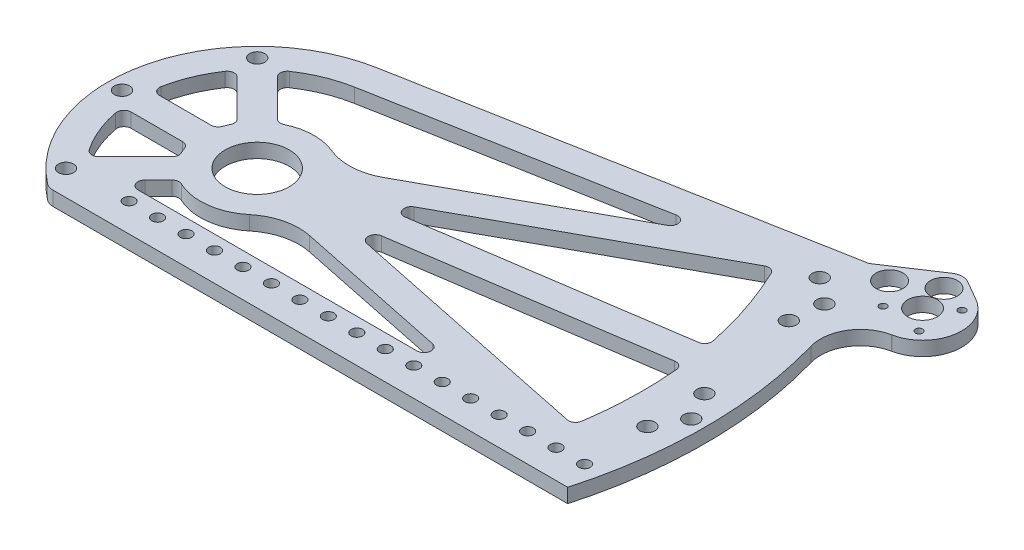
SolidWorks part; units mm, degrees
ref_plane "Front Plane" through (0, 0, 0) normal (0, 0, 1) x (1, 0, 0)
ref_plane "Top Plane" through (0, 0, 0) normal (0, 1, 0) x (1, 0, 0)
ref_plane "Right Plane" through (0, 0, 0) normal (1, 0, 0) x (0, 0, -1)
ref_plane "Plane1" through (0, 0, 0) normal (0, -1, 0) x (1, 0, 0)
sketch "Sketch1" plane through (0, 0, 0) normal (0, -1, 0) x (1, 0, 0)
  line L0 (231.775, 53.975) -> (-37.0265, 53.975)
  line L1 (-25.4, -65.7616) -> (-25.4, -230.9908)
  line L2 (238.125, 0) -> (238.125, 47.625)
  circle A0 centre (-60.325, 0) radius 3.3782
  circle A1 centre (-42.6562, 42.6562) radius 3.3782
  circle A2 centre (-42.6562, -42.6562) radius 3.3782
  circle A3 centre (0, -155.575) radius 3.3782
  circle A4 centre (0, -168.275) radius 3.3782
  circle A5 centre (0, -180.975) radius 3.3782
  circle A6 centre (0, -193.675) radius 3.3782
  circle A7 centre (0, -206.375) radius 3.3782
  circle A8 centre (0, -219.075) radius 3.3782
  circle A9 centre (59.536, -143.7326) radius 3.3782
  circle A10 centre (64.3961, -155.4658) radius 3.3782
  circle A11 centre (69.2561, -167.1991) radius 3.3782
  circle A12 centre (74.1162, -178.9324) radius 3.3782
  circle A13 centre (78.9763, -190.6656) radius 3.3782
  circle A14 centre (83.8364, -202.3989) radius 3.3782
  circle A15 centre (110.0081, -110.0081) radius 3.3782
  circle A16 centre (118.9884, -118.9884) radius 3.3782
  circle A17 centre (127.9686, -127.9686) radius 3.3782
  circle A18 centre (136.9489, -136.9489) radius 3.3782
  circle A19 centre (145.9292, -145.9292) radius 3.3782
  circle A20 centre (154.9094, -154.9094) radius 3.3782
  circle A21 centre (143.7326, -59.536) radius 3.3782
  circle A22 centre (155.4658, -64.3961) radius 3.3782
  circle A23 centre (167.1991, -69.2561) radius 3.3782
  circle A24 centre (178.9324, -74.1162) radius 3.3782
  circle A25 centre (190.6656, -78.9763) radius 3.3782
  circle A26 centre (202.3989, -83.8364) radius 3.3782
  circle A27 centre (155.575, 0) radius 3.3782
  circle A28 centre (168.275, 0) radius 3.3782
  circle A29 centre (180.975, 0) radius 3.3782
  circle A30 centre (193.675, 0) radius 3.3782
  circle A31 centre (206.375, 0) radius 3.3782
  circle A32 centre (219.075, 0) radius 3.3782
  circle A33 centre (0, 0) radius 14.2812
  circle A34 centre (148.6836, 12.7) radius 3.3782
  circle A35 centre (141.0863, -159.0468) radius 3.3782
  circle A36 centre (150.0365, -132.0759) radius 3.3782
  circle A37 centre (150.0666, -168.0271) radius 3.3782
  circle A38 centre (159.0167, -141.0562) radius 3.3782
  circle A39 centre (-12.7, -186.8262) radius 3.3782
  circle A40 centre (12.7, -174.0836) radius 3.3782
  circle A41 centre (-12.7, -199.5262) radius 3.3782
  circle A42 centre (12.7, -186.7836) radius 3.3782
  circle A43 centre (-12.7, -212.2262) radius 3.3782
  circle A44 centre (12.7, -199.4836) radius 3.3782
  circle A45 centre (-12.7, -224.9262) radius 3.3782
  circle A46 centre (12.7, -212.1836) radius 3.3782
  circle A47 centre (69.4822, -200.9315) radius 3.3782
  circle A48 centre (88.0723, -179.4387) radius 3.3782
  circle A49 centre (74.3423, -212.6648) radius 3.3782
  circle A50 centre (92.9324, -191.172) radius 3.3782
  circle A51 centre (50.0419, -153.9984) radius 3.3782
  circle A52 centre (68.632, -132.5056) radius 3.3782
  circle A53 centre (54.9019, -165.7317) radius 3.3782
  circle A54 centre (73.4921, -144.2389) radius 3.3782
  circle A55 centre (59.762, -177.465) radius 3.3782
  circle A56 centre (78.3522, -155.9722) radius 3.3782
  circle A57 centre (64.6221, -189.1982) radius 3.3782
  circle A58 centre (83.2123, -167.7055) radius 3.3782
  circle A59 centre (123.1258, -141.0863) radius 3.3782
  circle A60 centre (132.0759, -114.1154) radius 3.3782
  circle A61 centre (132.1061, -150.0666) radius 3.3782
  circle A62 centre (141.0562, -123.0957) radius 3.3782
  circle A63 centre (200.8922, -69.4659) radius 3.3782
  circle A64 centre (202.9446, -97.8088) radius 3.3782
  circle A65 centre (189.1589, -64.6058) radius 3.3782
  circle A66 centre (191.2114, -92.9487) radius 3.3782
  circle A67 centre (105.1653, -123.1258) radius 3.3782
  circle A68 centre (114.1154, -96.1549) radius 3.3782
  circle A69 centre (114.1456, -132.1061) radius 3.3782
  circle A70 centre (123.0957, -105.1352) radius 3.3782
  circle A71 centre (153.9591, -50.0256) radius 3.3782
  circle A72 centre (156.0115, -78.3685) radius 3.3782
  circle A73 centre (142.2258, -45.1655) radius 3.3782
  circle A74 centre (144.2783, -73.5084) radius 3.3782
  circle A75 centre (177.4256, -59.7457) radius 3.3782
  circle A76 centre (179.4781, -88.0886) radius 3.3782
  circle A77 centre (165.6923, -54.8856) radius 3.3782
  circle A78 centre (167.7448, -83.2286) radius 3.3782
  circle A79 centre (-12.7, -161.4262) radius 3.3782
  circle A80 centre (12.7, -148.6836) radius 3.3782
  circle A81 centre (-12.7, -174.1262) radius 3.3782
  circle A82 centre (12.7, -161.3836) radius 3.3782
  circle A83 centre (186.8262, -12.7) radius 3.3782
  circle A84 centre (174.0836, 12.7) radius 3.3782
  circle A85 centre (199.5262, -12.7) radius 3.3782
  circle A86 centre (186.7836, 12.7) radius 3.3782
  circle A87 centre (212.2262, -12.7) radius 3.3782
  circle A88 centre (199.4836, 12.7) radius 3.3782
  circle A89 centre (224.9262, -12.7) radius 3.3782
  circle A90 centre (212.1836, 12.7) radius 3.3782
  circle A91 centre (161.4262, -12.7) radius 3.3782
  circle A92 centre (174.1262, -12.7) radius 3.3782
  circle A93 centre (161.3836, 12.7) radius 3.3782
  circle A94 centre (225.425, 41.275) radius 2.5527
  circle A95 centre (212.725, 41.275) radius 2.5527
  circle A96 centre (200.025, 41.275) radius 2.5527
  circle A97 centre (187.325, 41.275) radius 2.5527
  circle A98 centre (174.625, 41.275) radius 2.5527
  circle A99 centre (161.925, 41.275) radius 2.5527
  circle A100 centre (149.225, 41.275) radius 2.5527
  circle A101 centre (136.525, 41.275) radius 2.5527
  circle A102 centre (123.825, 41.275) radius 2.5527
  circle A103 centre (111.125, 41.275) radius 2.5527
  circle A104 centre (98.425, 41.275) radius 2.5527
  circle A105 centre (73.025, 41.275) radius 2.5527
  circle A106 centre (85.725, 41.275) radius 2.5527
  circle A107 centre (60.325, 41.275) radius 2.5527
  circle A108 centre (47.625, 41.275) radius 2.5527
  circle A109 centre (34.925, 41.275) radius 2.5527
  circle A110 centre (22.225, 41.275) radius 2.5527
  circle A111 centre (9.525, 41.275) radius 2.5527
  circle A112 centre (-3.175, 41.275) radius 2.5527
  circle A113 centre (-15.875, 41.275) radius 2.5527
  circle A114 centre (-17.9605, 17.9605) radius 2.5527
  circle A115 centre (-17.9605, -17.9605) radius 2.5527
  circle A116 centre (17.9605, -17.9605) radius 2.5527
  circle A117 centre (17.9605, 17.9605) radius 2.5527
  circle A118 centre (52.1146, -6.35) radius 9.5885
  circle A119 centre (70.0751, 11.6105) radius 2.5527
  circle A120 centre (-17.9605, -34.5395) radius 2.5527
  circle A121 centre (17.9605, -70.4605) radius 2.5527
  circle A122 centre (70.0751, -24.3105) radius 2.5527
  circle A123 centre (34.154, -24.3105) radius 2.5527
  circle A124 centre (34.154, 11.6105) radius 2.5527
  circle A125 centre (0, -52.5) radius 19.177
  circle A126 centre (-17.9605, -70.4605) radius 4.1275
  circle A127 centre (17.9605, -34.5395) radius 4.1275
  arc A128 (-37.0265, 53.975) -> (-40.9241, 52.6382) centre (-37.0265, 47.625) ccw
  arc A129 (-40.9241, 52.6382) -> (-28.9891, -60.0432) centre (0, 0) ccw
  arc A130 (-28.9891, -60.0432) -> (-25.4, -65.7616) centre (-31.75, -65.7616) cw
  arc A131 (-25.4, -230.9908) -> (-19.5719, -237.3193) centre (-19.05, -230.9908) ccw
  arc A132 (-19.5719, -237.3193) -> (238.125, 0) centre (0, 0) ccw
  arc A133 (238.125, 47.625) -> (231.775, 53.975) centre (231.775, 47.625) ccw
extrude "Boss-Extrude1" add sketch "Sketch1" against normal blind 6.35
sketch "Sketch2" plane through (0, 6.35, 0) normal (0, 1, 0) x (1, 0, 0)
  circle A0 centre (0, 52.5) radius 19.177
  circle A1 centre (17.9605, 70.4605) radius 2.5527
  circle A2 centre (17.9605, 34.5395) radius 4.1275
  circle A3 centre (-17.9605, 34.5395) radius 2.5527
  circle A4 centre (-17.9605, 70.4605) radius 4.1275
  circle A5 centre (34.154, -11.6105) radius 2.5527
  circle A6 centre (52.1146, 6.35) radius 9.5885
  circle A7 centre (34.154, 24.3105) radius 2.5527
  circle A8 centre (70.0751, 24.3105) radius 2.5527
  circle A9 centre (70.0751, -11.6105) radius 2.5527
  circle A10 centre (17.9605, -17.9605) radius 2.5527
  circle A11 centre (-17.9605, -17.9605) radius 2.5527
  circle A12 centre (-17.9605, 17.9605) radius 2.5527
  circle A13 centre (17.9605, 17.9605) radius 2.5527
extrude "Boss-Extrude2" add sketch "Sketch2" against normal through all contours A4 | A3 | A12 | A11 | A10 | A9 | A6 | A2 | A0 | A8 | A7 | A5 | A1 | A13
sketch "Sketch3" plane through (0, 6.35, 0) normal (0, 1, 0) x (1, 0, 0)
  line L0 (0, 0) -> (167.7448, 83.2286) construction
  line L1 (0, 0) -> (123.1258, 141.0863) construction
  line L2 (186.8262, 12.7) -> (186.8262, -53.975) construction
  line L3 (231.775, -53.975) -> (-37.0265, -53.975) construction
  line L4 (0, 0) -> (186.8262, 12.7) construction
  line L6 (-28.9891, 60.0432) -> (-28.9891, 240.2011)
  line L7 (-28.9891, 240.2011) -> (143.8883, 240.2011)
  line L9 (92.9324, 191.172) -> (159.0167, 141.0562) construction
  line L12 (143.8883, 195.6216) -> (143.8883, 240.2011)
  line L14 (190.335, -61.1929) -> (235.0044, -61.1929)
  line L15 (241.8769, -21.6157) -> (241.8769, -61.1929)
  line L16 (241.8769, -61.1929) -> (235.0044, -61.1929)
  line L17 (173.283, 99.7245) -> (-12.0815, 65.5713)
  line L18 (145.5713, 94.6187) -> (182.0476, 82.6479) construction
  circle A0 centre (0, 0) radius 50.8 construction
  arc A3 (-12.0815, 65.5713) -> (-28.9891, 60.0432) centre (0, 0) ccw
  arc A4 (66.5215, 4.522) -> (43.8403, 50.2353) centre (0, 0) ccw construction
  arc A5 (190.335, -61.1929) -> (173.283, 99.7245) centre (0, 0) ccw
  arc A6 (241.8769, -21.6157) -> (143.8883, 195.6216) centre (0, 0) ccw
  dimension "D1" = 101.6
  dimension "D2" = 187.2574
extrude "Cut-Extrude1" cut sketch "Sketch3" against normal through all
sketch "Sketch4" plane through (0, 6.35, 0) normal (0, 1, 0) x (1, 0, 0)
  arc A2 (199.2831, 16.0694) -> (199.7123, 9.3269) centre (199.5262, 12.7) ccw
  arc A3 (188.0802, 67.8072) -> (190.264, 61.4135) centre (189.1589, 64.6058) ccw
  arc A4 (177.9641, 91.1086) -> (180.9408, 85.0435) centre (179.4781, 88.0886) ccw
  arc A7 (199.2831, 16.0694) -> (199.7123, 9.3269) centre (0, 0) cw
  arc A8 (177.9641, 91.1086) -> (180.9408, 85.0435) centre (0, 0) cw
  arc A10 (188.0802, 67.8072) -> (190.264, 61.4135) centre (0, 0) cw
  arc A11 (199.7122, -9.3295) -> (199.2829, -16.0722) centre (199.4836, -12.7) ccw
  arc A12 (199.2829, -16.0722) -> (199.7122, -9.3295) centre (0, 0) ccw
  arc A13 (199.7123, 9.3269) -> (190.264, 61.4135) centre (0, 0) ccw
extrude "Boss-Extrude3" add sketch "Sketch4" against normal up to surface (6.35 mm away) up to face at (-60.325, 0, 3.3782)
sketch "Sketch9" plane through (0, 6.35, 0) normal (0, 1, 0) x (1, 0, 0)
  line L0 (173.283, 99.7245) -> (195.6033, 114.5003)
  line L2 (173.283, 99.7245) -> (184.5174, 97.6189) construction
  line L3 (202.4991, 94.3534) -> (199.5713, 106.8418) construction
  line L4 (199.5713, 106.8418) -> (184.5174, 97.6189) construction
  line L5 (202.4991, 94.3534) -> (212.083, 102.3782) construction
  line L6 (202.4991, 94.3534) -> (210.5239, 84.7694) construction
  line L7 (202.2925, 114.6994) -> (211.2738, 109.4945)
  line L8 (186.046, 73.2045) -> (205.9408, 77.1951)
  arc A0 (192.5063, -53.975) -> (173.283, 99.7245) centre (0, 0) ccw construction
  circle A1 centre (184.5174, 97.6189) radius 6.0007
  circle A2 centre (199.5713, 106.8418) radius 6.0008
  circle A3 centre (202.4991, 94.3534) radius 12.5 construction
  circle A4 centre (212.083, 102.3782) radius 1.6
  circle A5 centre (210.5239, 84.7694) radius 1.6
  circle A6 centre (192.9151, 86.3286) radius 1.6
  arc A8 (173.283, 99.7245) -> (186.046, 73.2045) centre (0, 0) cw
  circle A9 centre (202.4991, 94.3534) radius 6.6
  arc A10 (205.9408, 77.1951) -> (211.2738, 109.4945) centre (202.4991, 94.3534) ccw
  arc A11 (202.2925, 114.6994) -> (195.6033, 114.5003) centre (199.1085, 109.2054) ccw
  point P1 (198.8862, 116.6735)
  dimension "D10" = 12.0015
  dimension "D11" = 12.0015
  dimension "D12" = 25
  dimension "D13" = 3.2
  dimension "D16" = 13.2
  dimension "D17" = 35
  dimension "D2" = 6.35
  dimension "D4" = 44.12
  dimension "D5" = 137.89
  dimension "D6" = 17.6545
  dimension "D7" = 12.827
  dimension "D8" = 11.43
  dimension "D9" = 71.7
  dimension "D15" = 90
  dimension "D14" = 3
extrude "Boss-Extrude4" add sketch "Sketch9" against normal up to surface (6.35 mm away) up to face at (-60.325, 0, 3.3782)
fillet "Fillet1" radius 17.78 1 edges at (186.046, 3.175, -73.2045)
sketch "Sketch10" plane through (0, 0, 0) normal (0, -1, 0) x (1, 0, 0)
  circle A0 centre (165.6923, -54.8856) radius 3.3782
  circle A1 centre (167.1991, -69.2561) radius 3.3782
  circle A2 centre (156.0115, -78.3685) radius 3.3782
  circle A3 centre (144.2783, -73.5084) radius 3.3782
  circle A4 centre (155.4658, -64.3961) radius 3.3782
  circle A5 centre (143.7326, -59.536) radius 3.3782
  circle A6 centre (153.9591, -50.0256) radius 3.3782
  circle A7 centre (142.2258, -45.1655) radius 3.3782
  circle A8 centre (161.4262, -12.7) radius 3.3782
  circle A9 centre (174.1262, -12.7) radius 3.3782
  circle A10 centre (155.575, 0) radius 3.3782
  circle A11 centre (168.275, 0) radius 3.3782
  circle A12 centre (180.975, 0) radius 3.3782
  circle A13 centre (148.6836, 12.7) radius 3.3782
  circle A14 centre (161.3836, 12.7) radius 3.3782
  circle A15 centre (174.0836, 12.7) radius 3.3782
extrude "Boss-Extrude5" add sketch "Sketch10" against normal through all
sketch "Sketch11" plane through (0, 0, 0) normal (0, -1, 0) x (1, 0, 0)
  line L3 (-42.6562, -42.6562) -> (0, 0) construction
  line L4 (0, 0) -> (-42.6562, 42.6562) construction
  line L5 (192.5063, 41.275) -> (-34.7804, 41.275)
  line L6 (-9.7802, -53.0815) -> (175.5843, -87.2348)
  line L8 (-9.7802, -53.0815) -> (130.9185, -79.0051)
  line L9 (0, 0) -> (-60.325, 0) construction
  line L10 (0, 0) -> (150.8176, -82.6716) construction
  line L11 (-33.4109, -42.3912) -> (-12.9001, -21.8803)
  line L12 (-12.9001, 21.8803) -> (-25.9447, 34.925)
  line L13 (0, 0) -> (168.4066, 34.925) construction
  line L14 (-42.3912, -33.4109) -> (-21.8803, -12.9001)
  line L16 (-21.8803, 12.9001) -> (-42.3912, 33.4109)
  line L17 (0, 0) -> (170.0978, -25.4416) construction
  line L18 (192.5063, 34.925) -> (-37.0265, 34.925)
  line L19 (-47.1463, -38.1661) -> (-4.4901, 4.4901) construction
  line L20 (-38.1661, -47.1463) -> (4.4901, -4.4901) construction
  line L21 (137.1357, 34.925) -> (-25.9447, 34.925)
  line L22 (4.4901, 4.4901) -> (-38.1661, 47.1463) construction
  line L23 (-24.5934, 6.35) -> (-53.6002, 6.35)
  line L24 (-24.5934, -6.35) -> (-53.6002, -6.35)
  line L25 (18.5136, -17.3898) -> (130.9185, -79.0051)
  line L28 (3.0523, 5.5683) -> (9.5844, 1.9877)
  line L31 (34.2764, -11.5474) -> (169.0425, -31.7044)
  line L32 (-3.0523, -5.5683) -> (147.7654, -88.2399) construction
  line L34 (34.2764, -11.5474) -> (153.7671, -77.0469)
  line L36 (36.1551, 1.0129) -> (169.5813, 28.6835)
  line L37 (3.0523, 5.5683) -> (153.8699, -77.1032) construction
  line L38 (36.1551, 1.0129) -> (170.9212, -19.1441)
  line L40 (22.7916, 11.2117) -> (137.1357, 34.925)
  arc A0 (-24.5934, -6.35) -> (-21.8803, -12.9001) centre (0, 0) ccw
  arc A4 (-12.9001, -21.8803) -> (18.5136, -17.3898) centre (0, 0) ccw
  arc A5 (-34.7804, 41.275) -> (-9.7802, -53.0815) centre (0, 0) ccw
  arc A6 (-42.3912, 33.4109) -> (-53.6002, 6.35) centre (0, 0) ccw
  arc A7 (165.387, -47.1984) -> (165.6038, 46.4321) centre (0, 0) ccw
  arc A8 (153.7671, -77.0469) -> (169.0425, -31.7044) centre (0, 0) ccw
  arc A9 (-21.8803, 12.9001) -> (-24.5934, 6.35) centre (0, 0) ccw
  arc A10 (-53.6002, -6.35) -> (-42.3912, -33.4109) centre (0, 0) ccw
  arc A11 (-33.4109, -42.3912) -> (-9.7802, -53.0815) centre (0, 0) ccw
  arc A12 (170.9212, -19.1441) -> (169.5813, 28.6835) centre (0, 0) ccw
  arc A13 (22.7916, 11.2117) -> (-12.9001, 21.8803) centre (0, 0) ccw
  point P6 (0, 6.35)
  point P12 (-60.325, 6.35)
  point P25 (0, -6.35)
  point P26 (-60.325, -6.35)
  point P29 (-4.4901, -4.4901)
  point P30 (-47.1463, 38.1661)
  point P45 (1.2895, -6.2177)
  point P48 (169.6961, 28.7073)
  point P49 (-0.9393, -6.2801)
  point P50 (169.1585, -31.7218)
  point P53 (-1.2895, 6.2177)
  point P54 (167.1172, 41.1427)
  point P55 (0.9393, 6.2801)
  point P56 (171.0372, -19.1615)
  dimension "D1" = 50.8
  dimension "D4" = 6.35
  dimension "D6" = 19.05
  dimension "D7" = 6.35
  dimension "D2" = 12.7
  dimension "D3" = 27.94
  dimension "D5" = 6.35
  dimension "D8" = 6.35
extrude "Cut-Extrude2" cut sketch "Sketch11" against normal through all contours L11 A11 L8 L25 A4 | L24 A10 L14 A0 | A9 L16 A6 L23 | A13 L40 L21 L12 | L38 A12 L36 | L34 A8 L31
fillet "Fillet2" radius 25.4 2 edges at (22.7916, 3.175, 11.2117) (18.5136, 3.175, -17.3898)
fillet "Fillet3" radius 3.175 20 edges at (169.5813, 3.175, 28.6835) (169.0425, 3.175, -31.7044) (153.7671, 3.175, -77.0469) (170.9212, 3.175, -19.1441) (34.2764, 3.175, -11.5474) (36.1551, 3.175, 1.0129) (137.1357, 3.175, 34.925) (130.9185, 3.175, -79.0051) (-53.6002, 3.175, -6.35) (-42.3912, 3.175, 33.4109) (-53.6002, 3.175, 6.35) (-42.3912, 3.175, -33.4109) (-33.4109, 3.175, -42.3912) (-25.9447, 3.175, 34.925) (-12.9001, 3.175, 21.8803) (-21.8803, 3.175, 12.9001) (-24.5934, 3.175, 6.35) (-24.5934, 3.175, -6.35) (-21.8803, 3.175, -12.9001) (-12.9001, 3.175, -21.8803)
